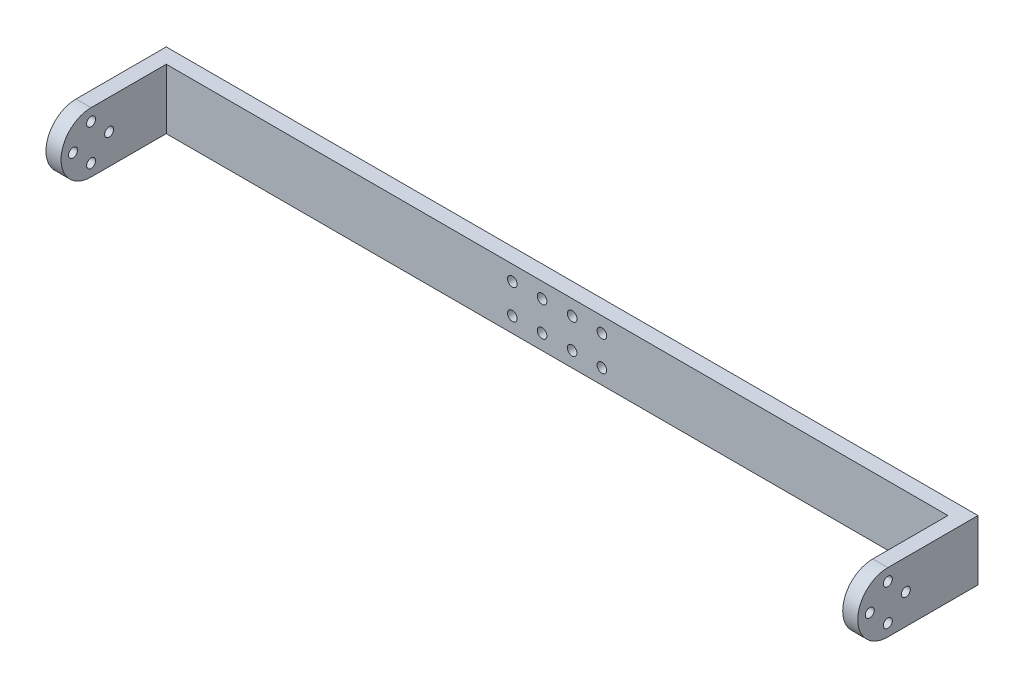
SolidWorks part; units mm, degrees
ref_plane "前视基准面" through (0, 0, 0) normal (0, 0, 1) x (1, 0, 0)
ref_plane "上视基准面" through (0, 0, 0) normal (0, 1, 0) x (1, 0, 0)
ref_plane "右视基准面" through (0, 0, 0) normal (1, 0, 0) x (0, 0, -1)
sketch "草图1" plane through (0, 0, 0) normal (0, 0, 1) x (1, 0, 0)
  line L1 (-135, 10) -> (135, 10)
  line L2 (-135, 10) -> (-135, -10)
  line L3 (-135, -10) -> (135, -10)
  line L4 (135, 10) -> (135, -10)
  line L5 (0, -10) -> (0, 10) construction
  line L6 (-135, 0) -> (135, 0) construction
  point P0 (0, 0)
  dimension "D1" = 270
  dimension "D2" = 20
extrude "凸台-拉伸1" add sketch "草图1" along normal blind 5
sketch "草图2" plane through (0, 0, 5) normal (0, 0, 1) x (1, 0, 0)
  line L0 (-135, -10) -> (135, -10) construction
  line L1 (-135, 10) -> (-130, 10)
  line L2 (-135, 10) -> (-135, -10)
  line L3 (-135, -10) -> (-130, -10)
  line L4 (-130, 10) -> (-130, -10)
  dimension "D1" = 5
extrude "凸台-拉伸2" add sketch "草图2" along normal blind 35
sketch "草图3" plane through (0, 0, 5) normal (0, 0, 1) x (1, 0, 0)
  line L0 (135, 10) -> (-130, 10) construction
  line L1 (135, -10) -> (130, -10)
  line L2 (135, -10) -> (135, 10)
  line L3 (135, 10) -> (130, 10)
  line L4 (130, -10) -> (130, 10)
  dimension "D1" = 5
extrude "凸台-拉伸3" add sketch "草图3" along normal blind 35
sketch "草图4" plane through (0, 0, 0) normal (0, 0, -1) x (-1, 0, 0)
  line L0 (0, 0) -> (50.5424, 0) construction
  line L1 (0, 0) -> (0, -4.3828) construction
  circle A0 centre (5, 4.95) radius 1.6
  circle A1 centre (14.9, 4.95) radius 1.6
  circle A2 centre (-14.9, 4.95) radius 1.6
  circle A3 centre (-5, 4.95) radius 1.6
  circle A4 centre (14.9, -4.95) radius 1.6
  circle A5 centre (5, -4.95) radius 1.6
  circle A6 centre (-5, -4.95) radius 1.6
  circle A7 centre (-14.9, -4.95) radius 1.6
  dimension "D1" = 3.2
  dimension "D3" = 3.2
  dimension "D2" = 5
  dimension "4.95" = 4.95
  dimension "D4" = 4.95
  dimension "D5" = 14.9
extrude "切除-拉伸1" cut sketch "草图4" against normal blind 35
sketch "草图5" plane through (135, 0, 0) normal (1, 0, 0) x (0, 0, -1)
  line L0 (-40, -10) -> (-40, 10) construction
  line L1 (-40, 10) -> (0, 10) construction
  line L2 (-30, 10) -> (-40, 10)
  line L3 (-40, 10) -> (-40, -10)
  line L4 (-40, -10) -> (-30, -10)
  arc A0 (-30, 10) -> (-30, -10) centre (-30, 0) ccw
  line M4 (0, 10) -> (-40, 10)
  line M5 (-40, 10) -> (-40, -10)
  line M6 (-40, -10) -> (0, -10)
  dimension "D2" = 20
  dimension "D1" = 10
extrude "切除-拉伸2" cut sketch "草图5" against normal through all contours A0 M4 M5 | A0 L3 M6
sketch "草图6" plane through (-135, 0, 0) normal (-1, 0, 0) x (0, 0, 1)
  line L0 (30, 10) -> (30, -10)
  circle A0 centre (30, 0) radius 6 construction
  circle A1 centre (30, 6) radius 1.5
  circle A2 centre (36, 0) radius 1.5
  circle A3 centre (30, -6) radius 1.5
  circle A4 centre (24, 0) radius 1.5
  dimension "D1" = 12
  dimension "D2" = 3
  dimension "D3" = 3
  dimension "D4" = 3
  dimension "D5" = 3
extrude "切除-拉伸3" cut sketch "草图6" against normal through all contours L0 A3 | A4 | A2 | L0 A1 | L0 A1 | L0 A3
